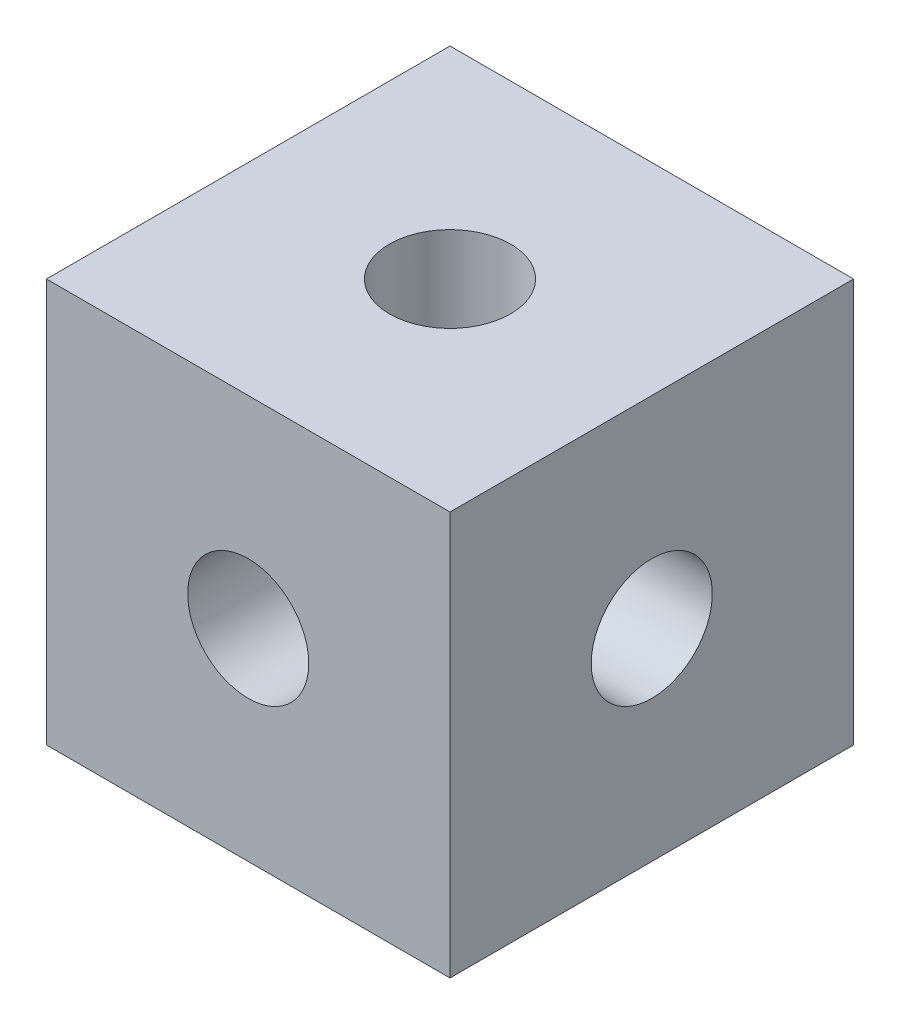
SolidWorks part; units mm, degrees
ref_plane "前视基准面" through (0, 0, 0) normal (0, 0, 1) x (1, 0, 0)
ref_plane "上视基准面" through (0, 0, 0) normal (0, 1, 0) x (1, 0, 0)
ref_plane "右视基准面" through (0, 0, 0) normal (1, 0, 0) x (0, 0, -1)
sketch "草图2" plane through (0, 0, 0) normal (0, 0, 1) x (1, 0, 0)
  line L1 (-5, -5) -> (5, -5)
  line L2 (-5, -5) -> (-5, 5)
  line L3 (-5, 5) -> (5, 5)
  line L4 (5, -5) -> (5, 5)
  line L5 (-5, -5) -> (5, 5) construction
  line L6 (-5, 5) -> (5, -5) construction
  circle A0 centre (0, 0) radius 1.5
  point P0 (0, 0)
  dimension "D1" = 3
  dimension "D2" = 10
  dimension "D3" = 10
extrude "凸台-拉伸1" add sketch "草图2" along normal blind 10
sketch "草图3" plane through (0, 5, 0) normal (0, 1, 0) x (1, 0, 0)
  line L0 (-5, 0) -> (5, -10) construction
  circle A0 centre (0, -5) radius 1.5
  dimension "D1" = 3
extrude "切除-拉伸1" cut sketch "草图3" against normal blind 10
sketch "草图4" plane through (-5, 0, 0) normal (-1, 0, 0) x (0, 0, 1)
  line L0 (0, 5) -> (10, -5) construction
  circle A0 centre (5, 0) radius 1.5
  dimension "D1" = 3
extrude "切除-拉伸2" cut sketch "草图4" against normal blind 10
